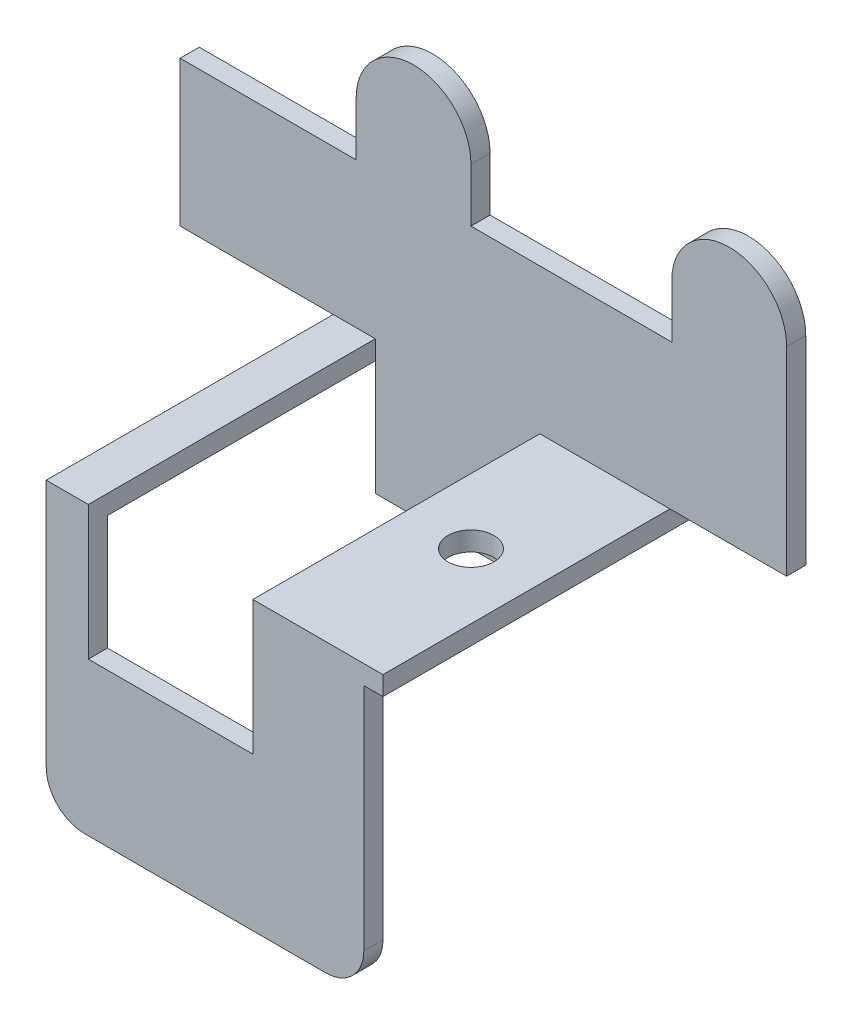
SolidWorks part; units mm, degrees
material "1023 Carbon Steel Sheet (SS)"
ref_plane "Front Plane" through (0, 0, 0) normal (0, 0, 1) x (1, 0, 0)
ref_plane "Top Plane" through (0, 0, 0) normal (0, 1, 0) x (1, 0, 0)
ref_plane "Right Plane" through (0, 0, 0) normal (1, 0, 0) x (0, 0, -1)
sketch "Sketch1" plane through (0, 0, 0) normal (0, 0, 1) x (1, 0, 0)
  line L0 (0, 0) -> (0, 9.652)
  line L1 (0, 9.652) -> (11.684, 9.652)
  line L2 (11.684, 9.652) -> (11.684, 13.208)
  line L3 (15.494, 13.208) -> (36.449, 13.208) construction
  line L4 (19.304, 13.208) -> (19.304, 9.652)
  line L5 (32.639, 13.208) -> (32.639, 9.652)
  line L6 (40.259, 13.208) -> (40.259, 9.652)
  line L7 (19.304, 9.652) -> (32.639, 9.652)
  line L8 (40.259, 9.652) -> (40.259, 0)
  line L9 (40.259, 0) -> (23.876, 0)
  line L10 (23.876, 0) -> (23.876, -8.89)
  line L11 (23.876, -8.89) -> (12.954, -8.89)
  line L12 (12.954, -8.89) -> (12.954, 0)
  line L13 (12.954, 0) -> (0, 0)
  arc A0 (11.684, 13.208) -> (19.304, 13.208) centre (15.494, 13.208) cw
  arc A1 (40.259, 13.208) -> (32.639, 13.208) centre (36.449, 13.208) ccw
  dimension "D3" = 7.62
  dimension "D4" = 3.81
  dimension "D7" = 16.383
  dimension "D1" = 11.684
  dimension "D2" = 9.652
  dimension "D5" = 3.556
  dimension "D6" = 20.955
  dimension "D8" = 10.922
  dimension "D9" = 8.89
extrude "Boss-Extrude1" add sketch "Sketch1" along normal blind 1.27
sketch "Sketch4" plane through (0, 0, 0) normal (0, 0, 1) x (1, 0, 0)
  line L1 (23.876, 0) -> (32.512, 0)
  line L2 (23.876, 0) -> (23.876, -1.27)
  line L3 (23.876, -1.27) -> (32.512, -1.27)
  line L4 (32.512, 0) -> (32.512, -1.27)
  line L5 (12.954, 0) -> (10.16, 0)
  line L6 (12.954, 0) -> (12.954, -1.27)
  line L7 (12.954, -1.27) -> (10.16, -1.27)
  line L8 (10.16, 0) -> (10.16, -1.27)
  dimension "D1" = 8.636
  dimension "D2" = 1.27
  dimension "D3" = 1.27
  dimension "D4" = 2.794
extrude "Boss-Extrude2" add sketch "Sketch4" along normal blind 20.32
sketch "Sketch5" plane through (0, -1.27, 0) normal (0, -1, 0) x (1, 0, 0)
  line L0 (12.954, 20.32) -> (12.954, 1.27) construction
  line L1 (10.16, 20.32) -> (12.954, 20.32)
  line L2 (10.16, 20.32) -> (10.16, 19.05)
  line L3 (10.16, 19.05) -> (12.954, 19.05)
  line L4 (12.954, 20.32) -> (12.954, 19.05)
  line L6 (23.876, 20.32) -> (31.242, 20.32)
  line L7 (23.876, 20.32) -> (23.876, 19.05)
  line L8 (23.876, 19.05) -> (31.242, 19.05)
  line L9 (31.242, 20.32) -> (31.242, 19.05)
  dimension "D1" = 1.27
  dimension "D2" = 7.366
  dimension "D3" = 1.27
extrude "Boss-Extrude3" add sketch "Sketch5" along normal blind 7.62
sketch "Sketch6" plane through (0, 0, 19.05) normal (0, 0, -1) x (-1, 0, 0)
  line L1 (-10.16, -8.89) -> (-31.242, -8.89)
  line L2 (-10.16, -8.89) -> (-10.16, -16.51)
  line L3 (-12.7, -19.05) -> (-28.702, -19.05)
  line L4 (-31.242, -8.89) -> (-31.242, -16.51)
  arc A0 (-28.702, -19.05) -> (-31.242, -16.51) centre (-28.702, -16.51) cw
  arc A1 (-12.7, -19.05) -> (-10.16, -16.51) centre (-12.7, -16.51) ccw
  point P7 (-31.242, -19.05)
  point P10 (-10.16, -19.05)
  dimension "D3" = 2.54
  dimension "D1" = 10.16
  dimension "D2" = 21.082
extrude "Boss-Extrude4" add sketch "Sketch6" against normal blind 1.27
sketch "Sketch7" plane through (0, -1.27, 0) normal (0, -1, 0) x (1, 0, 0)
  line L0 (28.194, 0) -> (28.194, 23.6197) construction
  line L1 (23.876, 0) -> (32.512, 0) construction
  circle A0 centre (28.194, 10.16) radius 1.524
  dimension "D1" = 3.048
  dimension "D2" = 10.16
extrude "Cut-Extrude1" cut sketch "Sketch7" against normal through all
